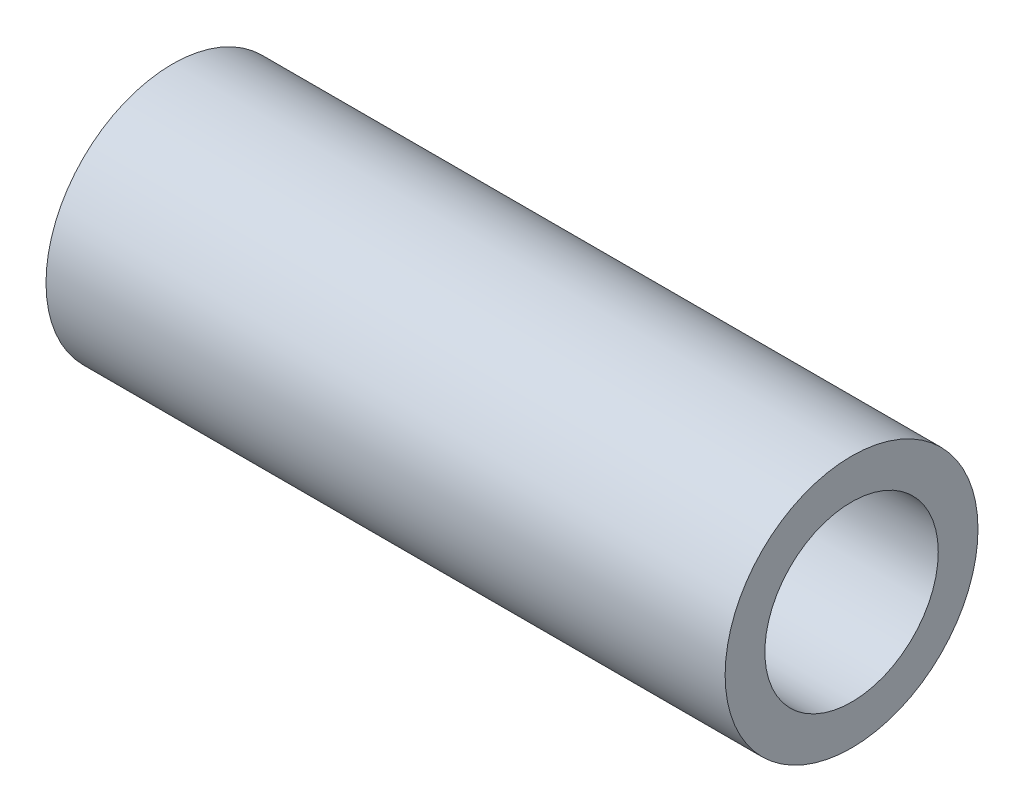
SolidWorks part; units mm, degrees
ref_plane "Front Plane" through (0, 0, 0) normal (0, 0, 1) x (1, 0, 0)
ref_plane "Top Plane" through (0, 0, 0) normal (0, 1, 0) x (1, 0, 0)
ref_plane "Right Plane" through (0, 0, 0) normal (1, 0, 0) x (0, 0, -1)
sketch "Sketch1" plane through (0, 0, 0) normal (1, 0, 0) x (0, 0, -1)
  circle A0 centre (0, 0) radius 3.048
  circle A1 centre (0, 0) radius 4.445
  dimension "D1" = 6.096
  dimension "D2" = 8.89
extrude "Boss-Extrude1" add sketch "Sketch1" along normal blind 23.876 contours A1 A0
